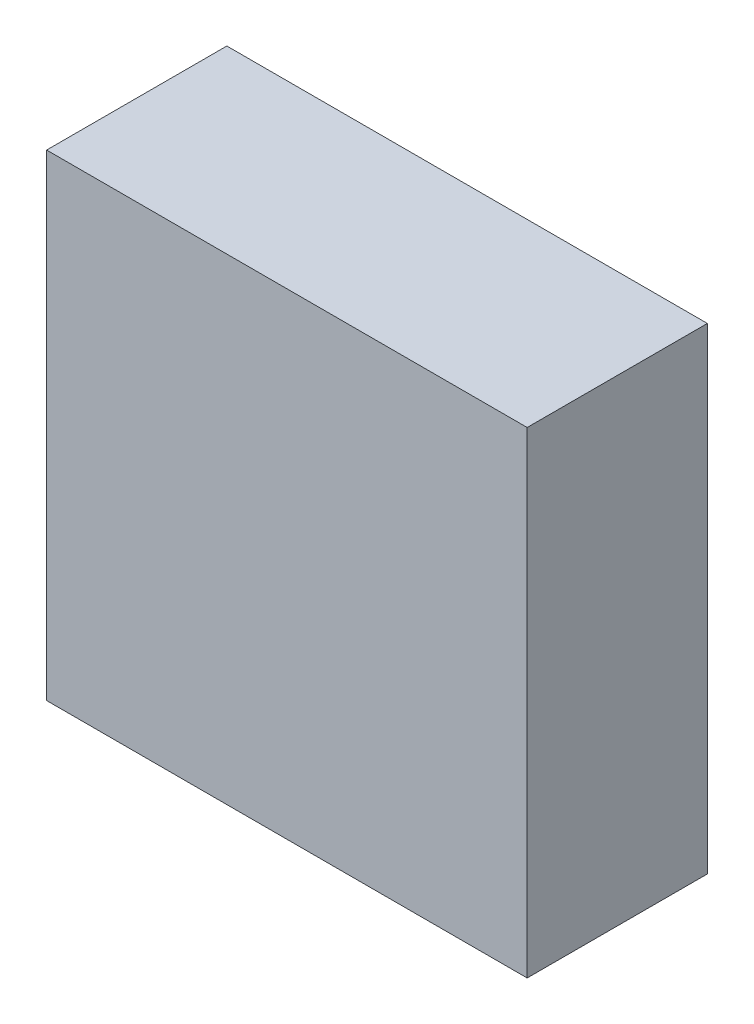
SolidWorks part; units mm, degrees
ref_plane "Front Plane" through (0, 0, 0) normal (0, 0, 1) x (1, 0, 0)
ref_plane "Top Plane" through (0, 0, 0) normal (0, 1, 0) x (1, 0, 0)
ref_plane "Right Plane" through (0, 0, 0) normal (1, 0, 0) x (0, 0, -1)
sketch "Sketch1" plane through (0, 0, 0) normal (0, 0, 1) x (1, 0, 0)
  line L1 (-64, 63.5) -> (64, 63.5)
  line L2 (-64, 63.5) -> (-64, -63.5)
  line L3 (-64, -63.5) -> (64, -63.5)
  line L4 (64, 63.5) -> (64, -63.5)
  line L5 (-64, 63.5) -> (64, -63.5) construction
  line L6 (-64, -63.5) -> (64, 63.5) construction
  point P0 (0, 0)
  dimension "D1" = 128
  dimension "D2" = 127
extrude "Boss-Extrude1" add sketch "Sketch1" along normal blind 48
